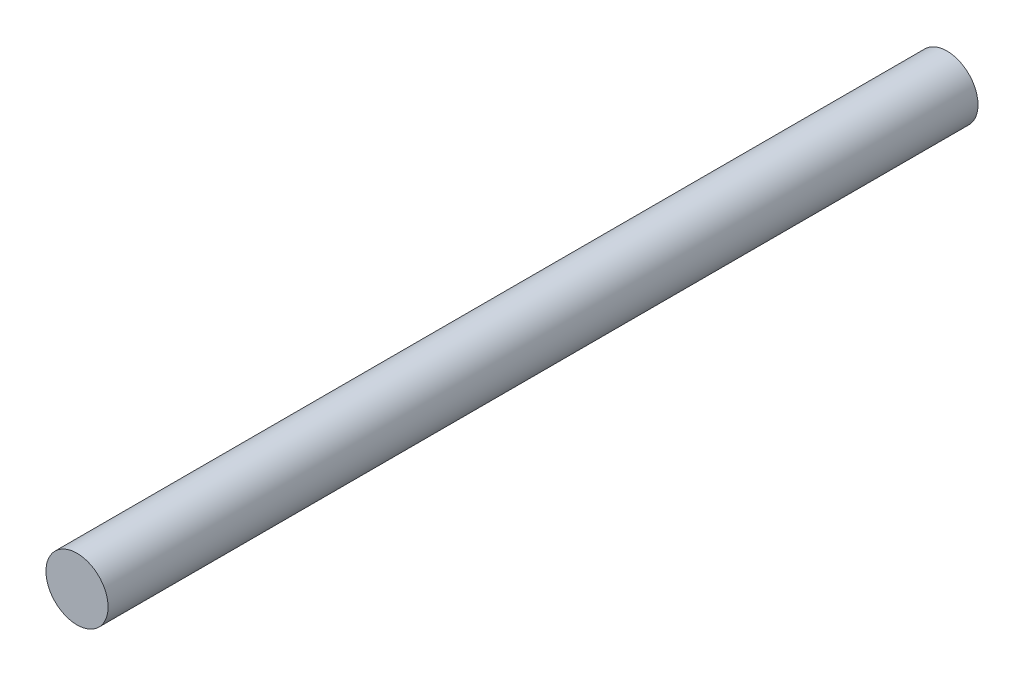
SolidWorks part; units mm, degrees
ref_plane "Front Plane" through (0, 0, 0) normal (0, 0, 1) x (1, 0, 0)
ref_plane "Top Plane" through (0, 0, 0) normal (0, 1, 0) x (1, 0, 0)
ref_plane "Right Plane" through (0, 0, 0) normal (1, 0, 0) x (0, 0, -1)
sketch "Sketch1" plane through (0, 0, 0) normal (0, 0, 1) x (1, 0, 0)
  circle A0 centre (0, 0) radius 2.5
extrude "Boss-Extrude1" add sketch "Sketch1" along normal blind 70
ref_plane "Plane1" through (0, 0, 54) normal (0, 0, 1) x (1, 0, 0)
sketch "Sketch2" plane through (0, 0, 54) normal (0, 0, 1) x (1, 0, 0)
  circle A0 centre (0, 0) radius 2.5
